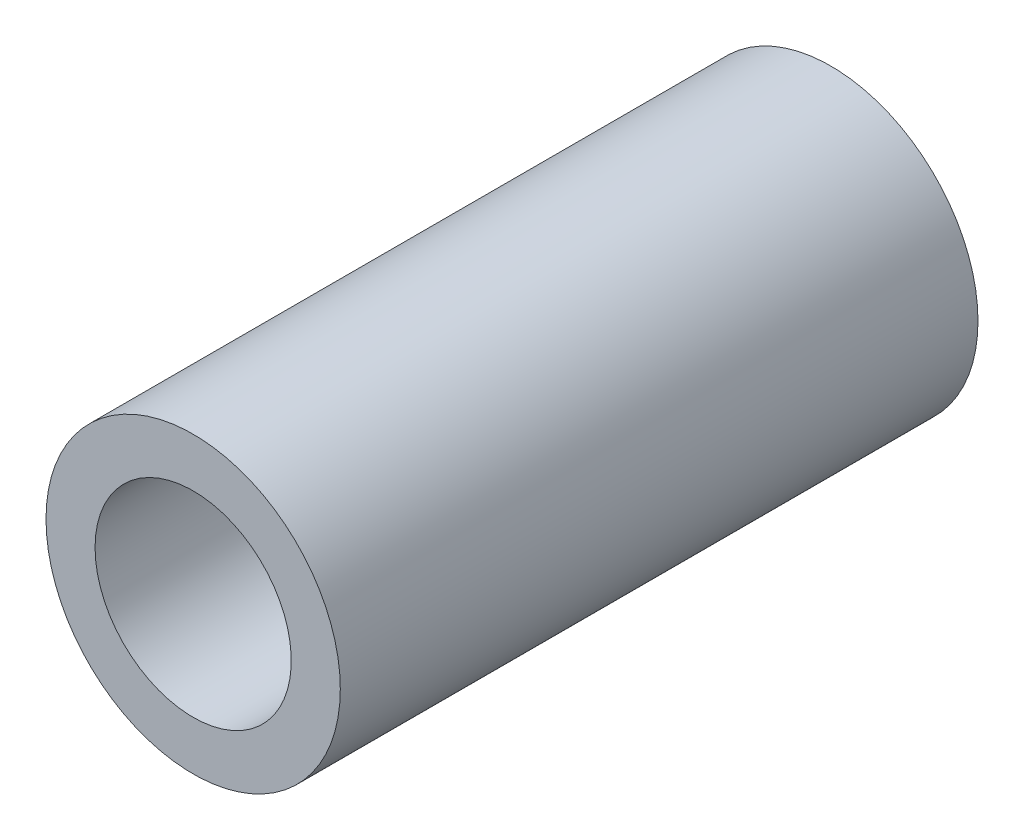
SolidWorks part; units mm, degrees
ref_plane "Plan de face" through (0, 0, 0) normal (0, 0, 1) x (1, 0, 0)
ref_plane "Plan de dessus" through (0, 0, 0) normal (0, 1, 0) x (1, 0, 0)
ref_plane "Plan de droite" through (0, 0, 0) normal (1, 0, 0) x (0, 0, -1)
sketch "Esquisse1" plane through (0, 0, 0) normal (0, 0, 1) x (1, 0, 0)
  circle A0 centre (0, 0) radius 3
  circle A1 centre (0, 0) radius 2
  dimension "D1" = 6
  dimension "D2" = 4
extrude "Boss.-Extru.1" add sketch "Esquisse1" along normal blind 13
